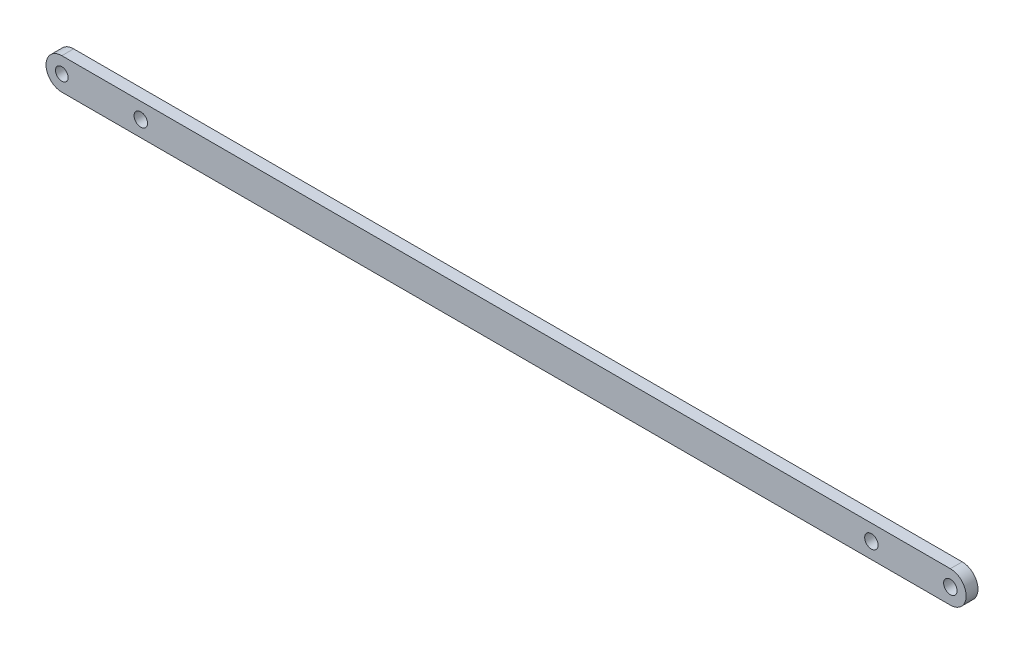
SolidWorks part; units mm, degrees
ref_plane "前视基准面" through (0, 0, 0) normal (0, 0, 1) x (1, 0, 0)
ref_plane "上视基准面" through (0, 0, 0) normal (0, 1, 0) x (1, 0, 0)
ref_plane "右视基准面" through (0, 0, 0) normal (1, 0, 0) x (0, 0, -1)
sketch "草图1" plane through (0, 0, 0) normal (0, 0, 1) x (1, 0, 0)
  line L0 (-53.8502, 4) -> (171.1498, 4)
  line L1 (-53.8502, -4) -> (171.1498, -4)
  arc A4 (-53.8502, 4) -> (-53.8502, -4) centre (-53.8502, 0) ccw
  circle A5 centre (-53.8502, 0) radius 1.6
  circle A12 centre (171.1498, 0) radius 4 construction
  circle A13 centre (171.1498, 0) radius 1.7 construction
  arc A14 (171.1498, 4) -> (171.1498, -4) centre (171.1498, 0) cw
  arc A17 (171.1498, 1.7) -> (171.1498, -1.7) centre (171.1498, 0) cw
  circle A18 centre (171.1498, 0) radius 1.7
  circle A19 centre (151.1498, 0) radius 1.7
  circle A20 centre (-33.8502, 0) radius 1.7
  point P15 (35.3474, 0)
  point P22 (0, 0)
  dimension "D1" = 225
  dimension "D2" = 225
  dimension "D3" = 20
  dimension "D4" = 20
  dimension "D7" = 8
  dimension "D8" = 3.2
extrude "凸台-拉伸1" add sketch "草图1" along normal blind 3 contours A14 L0 A4 L1 A18 A17 A5
